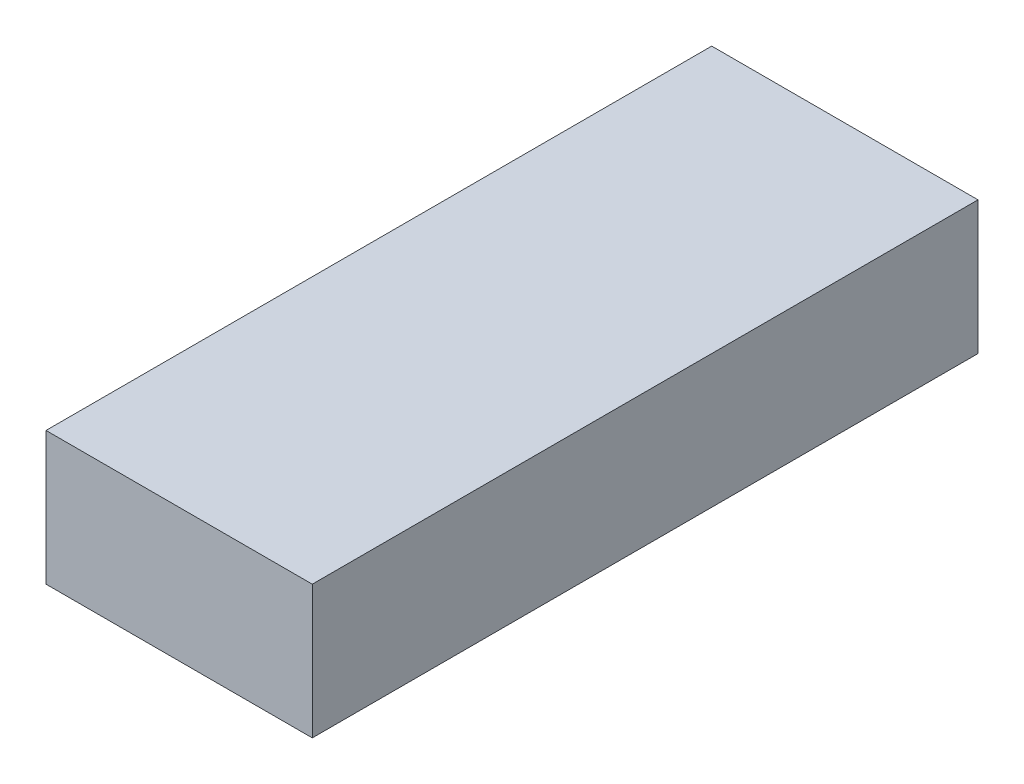
SolidWorks part; units mm, degrees
material "Beech"
ref_plane "Front Plane" through (0, 0, 0) normal (0, 0, 1) x (1, 0, 0)
ref_plane "Top Plane" through (0, 0, 0) normal (0, 1, 0) x (1, 0, 0)
ref_plane "Right Plane" through (0, 0, 0) normal (1, 0, 0) x (0, 0, -1)
sketch "Sketch1" plane through (0, 0, 0) normal (0, 1, 0) x (1, 0, 0)
  line L1 (0, 0) -> (304.8, 0)
  line L2 (0, 0) -> (0, 304.8)
  line L3 (0, 304.8) -> (304.8, 304.8)
  line L4 (304.8, 0) -> (304.8, 304.8)
  dimension "D1" = 304.8
  dimension "D2" = 304.8
extrude "Boss-Extrude1" add sketch "Sketch1" along normal blind 6.35
sketch "Sketch2" plane through (0, 6.35, 0) normal (0, 1, 0) x (1, 0, 0)
  line L1 (304.8, 304.8) -> (0, 304.8) construction
  line L2 (12.7, 304.8) -> (12.7, 273.05)
  line L3 (12.7, 273.05) -> (0, 273.05)
  line L4 (0, 304.8) -> (0, 0) construction
  line L6 (0, 273.05) -> (0, 0)
  line L7 (0, 0) -> (304.8, 0)
  line L8 (304.8, 0) -> (304.8, 304.8)
  line L9 (304.8, 304.8) -> (12.7, 304.8)
  dimension "D1" = 12.7
  dimension "D2" = 31.75
extrude "Cut-Extrude2" cut sketch "Sketch2" against normal blind 6.35 contours L3 L6 L7 L8 L9 L2
